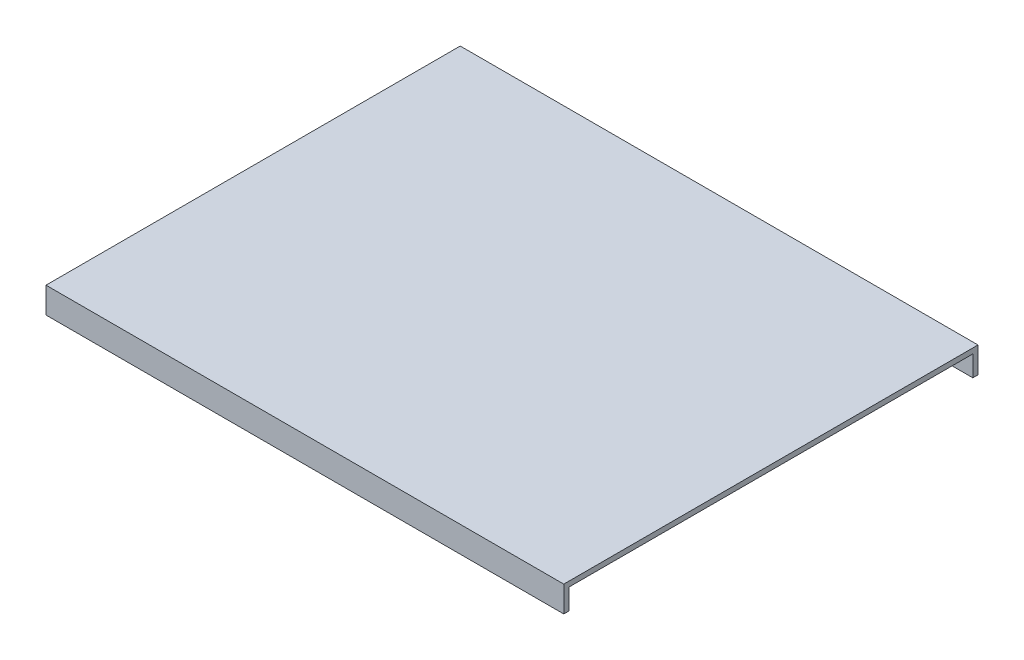
SolidWorks part; units mm, degrees
ref_plane "Ebene vorne" through (0, 0, 0) normal (0, 0, 1) x (1, 0, 0)
ref_plane "Ebene oben" through (0, 0, 0) normal (0, 1, 0) x (1, 0, 0)
ref_plane "Ebene rechts" through (0, 0, 0) normal (1, 0, 0) x (0, 0, -1)
sketch "Skizze1" plane through (0, 0, 0) normal (0, 0, 1) x (1, 0, 0)
  line L1 (0, 0) -> (1000, 0)
  line L2 (0, 0) -> (0, 50)
  line L3 (0, 50) -> (1000, 50)
  line L4 (1000, 0) -> (1000, 50)
  dimension "D1" = 50
  dimension "D2" = 1000
extrude "Aufsatz-Linear austragen1" add sketch "Skizze1" along normal blind 800
sketch "Skizze2" plane through (1000, 0, 0) normal (1, 0, 0) x (0, 0, -1)
  line L0 (-800, 0) -> (0, 0) construction
  line L1 (-790, 0) -> (-10, 0)
  line L2 (-790, 0) -> (-790, 40)
  line L3 (-790, 40) -> (-10, 40)
  line L4 (-10, 0) -> (-10, 40)
  line L5 (-800, 0) -> (-800, 50) construction
  line L6 (-800, 50) -> (0, 50) construction
  line L7 (0, 0) -> (0, 50) construction
  dimension "D1" = 10
  dimension "D2" = 10
  dimension "D3" = 10
extrude "Schnitt-Linear austragen1" cut sketch "Skizze2" against normal through all
